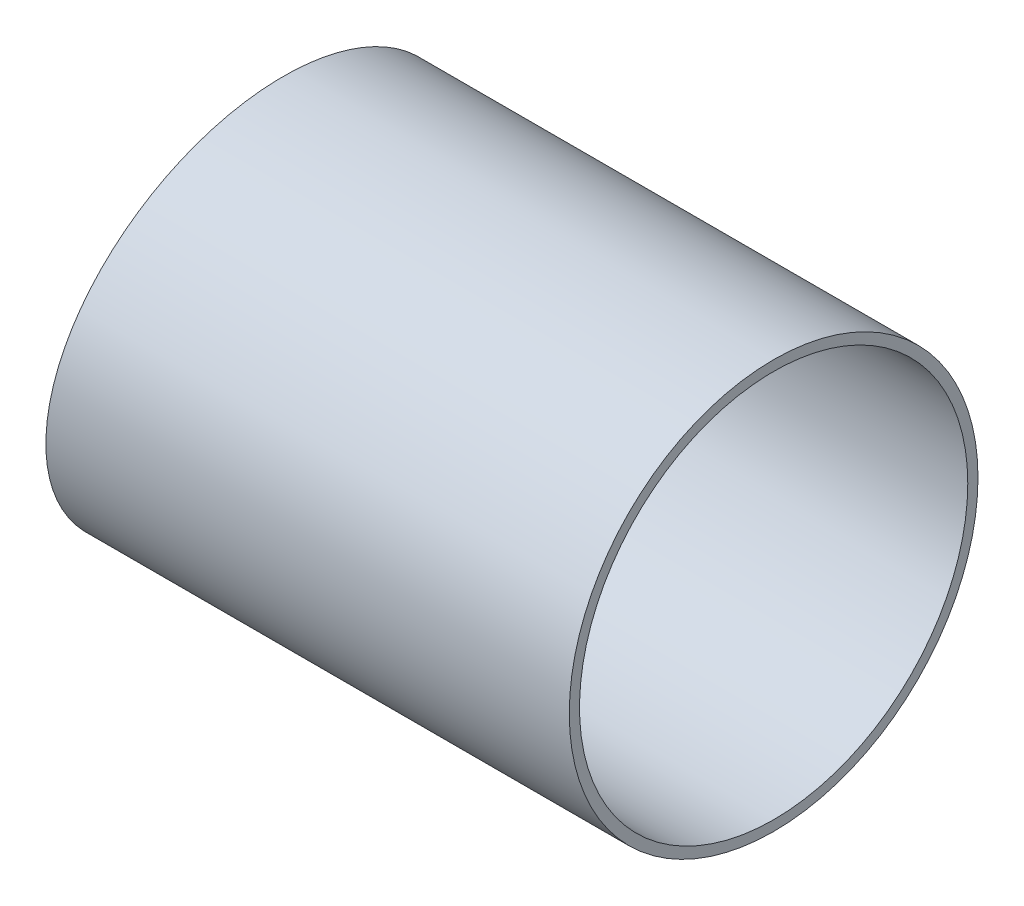
SolidWorks part; units mm, degrees
ref_plane "Alzado" through (0, 0, 0) normal (0, 0, 1) x (1, 0, 0)
ref_plane "Planta" through (0, 0, 0) normal (0, 1, 0) x (1, 0, 0)
ref_plane "Vista lateral" through (0, 0, 0) normal (1, 0, 0) x (0, 0, -1)
sketch "Croquis1" plane through (0, 0, 0) normal (1, 0, 0) x (0, 0, -1)
  circle A0 centre (0, 0) radius 50
  dimension "D1" = 100
extrude "Extruir-Lámina1" add sketch "Croquis1" along normal blind 135 thin thin type one direction reverse wall 2.5
sketch "Croquis6" plane through (0, 0, 0) normal (0, 0, 1) x (1, 0, 0)
  line L0 (0, -50) -> (0, 50)
  line L1 (0, -55) -> (0, 55) construction
  line L2 (0, 50) -> (0, -50) construction
  line L3 (0, 50) -> (15, 50)
  line L4 (15, 50) -> (0, -50)
  dimension "D1" = 15
extrude "Cortar-Extruir1" cut sketch "Croquis6" against normal through all both and the other way through all
